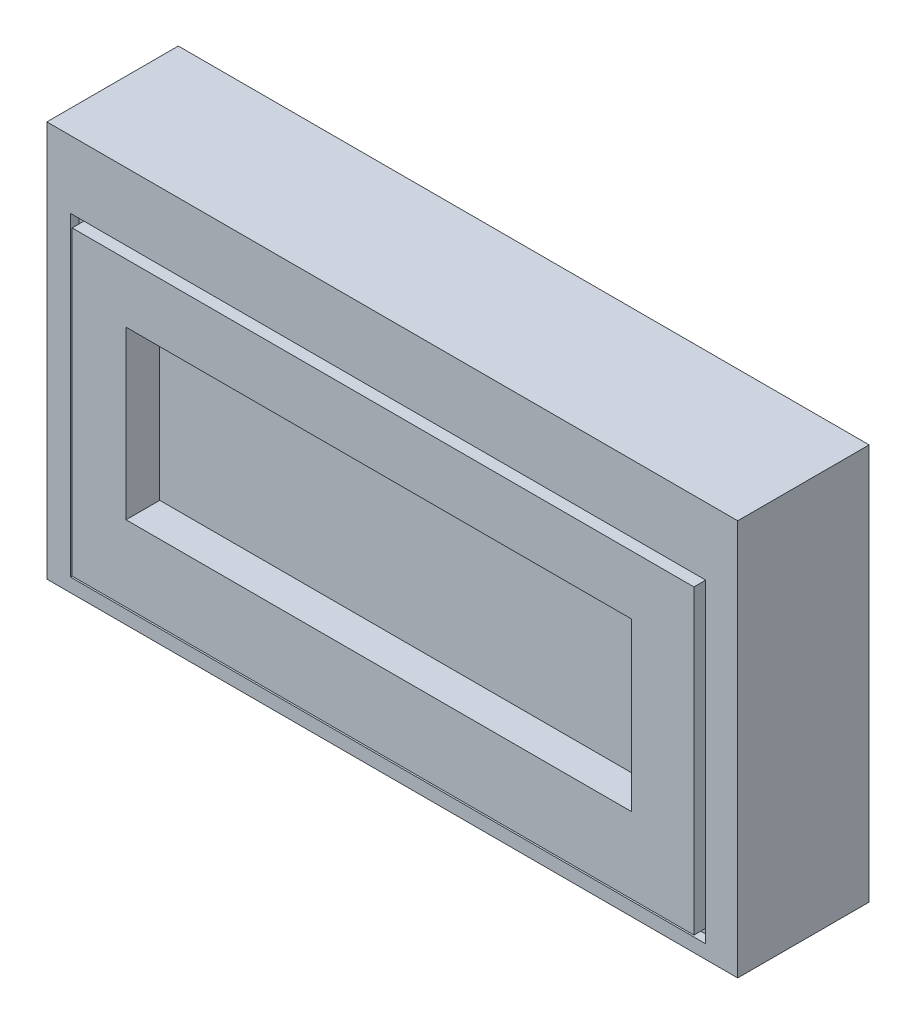
SolidWorks part; units mm, degrees
ref_plane "Alzado" through (0, 0, 0) normal (0, 0, 1) x (1, 0, 0)
ref_plane "Planta" through (0, 0, 0) normal (0, 1, 0) x (1, 0, 0)
ref_plane "Vista lateral" through (0, 0, 0) normal (1, 0, 0) x (0, 0, -1)
sketch "Croquis1" plane through (0, 0, 0) normal (0, 0, 1) x (1, 0, 0)
  line L1 (-43.4234, 226.9304) -> (366.5766, 226.9304)
  line L2 (-43.4234, 226.9304) -> (-43.4234, -8.0696)
  line L3 (-43.4234, -8.0696) -> (366.5766, -8.0696)
  line L4 (366.5766, 226.9304) -> (366.5766, -8.0696)
extrude "Saliente-Extruir1" add sketch "Croquis1" along normal blind 78
sketch "Croquis2" plane through (0, 0, 78) normal (0, 0, 1) x (1, 0, 0)
  line L0 (154.0772, 186.9304) -> (154.0772, 226.9304) construction
  line L1 (366.5766, 226.9304) -> (-43.4234, 226.9304) construction
  line L2 (366.5766, 109.4304) -> (347.5766, 109.4304) construction
  line L3 (366.5766, -8.0696) -> (366.5766, 226.9304) construction
  line L4 (161.5766, -8.0696) -> (161.5766, 0.9304) construction
  line L5 (-43.4234, -8.0696) -> (366.5766, -8.0696) construction
  line L6 (-43.4234, 109.4304) -> (-29.4234, 109.4304) construction
  line L7 (-43.4234, 226.9304) -> (-43.4234, -8.0696) construction
  line L8 (347.5766, 186.9304) -> (-29.4234, 186.9304)
  line L9 (-29.4234, 186.9304) -> (-29.4234, 0)
  line L10 (-29.4234, 0) -> (347.5766, 0)
  line L11 (347.5766, 0) -> (347.5766, 186.9304)
extrude "Cortar-Extruir1" cut sketch "Croquis2" against normal blind 5
sketch "Croquis3" plane through (0, 0, 73) normal (0, 0, 1) x (1, 0, 0)
  line L0 (343.5766, 182.9304) -> (-25.4234, 4) construction
  line L1 (-25.4234, 182.9304) -> (343.5766, 182.9304)
  line L2 (-25.4234, 182.9304) -> (-25.4234, 4)
  line L3 (-25.4234, 4) -> (343.5766, 4)
  line L4 (343.5766, 182.9304) -> (343.5766, 4)
  line L5 (347.5766, 186.9304) -> (-29.4234, 0) construction
  line L6 (159.0766, 93.4652) -> (179.0059, 93.4652) construction
  line L7 (179.0059, 93.4652) -> (139.6808, 93.4652) construction
  line L8 (347.5766, 0) -> (347.5766, 186.9304) construction
  line L9 (-29.4234, 0) -> (347.5766, 0) construction
  line L10 (347.5766, 186.9304) -> (-29.4234, 186.9304) construction
  line L11 (-29.4234, 186.9304) -> (-29.4234, 0) construction
  dimension "D1" = 4
  dimension "D2" = 4
  dimension "D3" = 4
  dimension "D4" = 4
extrude "Saliente-Extruir2" add sketch "Croquis3" along normal blind 8
sketch "Croquis4" plane through (0, 0, 78) normal (0, 0, 1) x (1, 0, 0)
  line L0 (-43.4234, -8.0696) -> (55.5766, -8.0696) construction
  line L1 (-43.4234, -8.0696) -> (366.5766, -8.0696) construction
  line L2 (55.5766, -8.0696) -> (55.5766, 92.9304) construction
  circle A0 centre (55.5766, 92.9304) radius 1
sketch "Croquis5" plane through (0, 0, 81) normal (0, 0, 1) x (1, 0, 0)
  line L0 (55.5766, 92.9304) -> (55.5766, 48.9304) construction
  line L1 (55.5766, -8.0696) -> (55.5766, 92.9304) construction
  line L2 (55.5766, 48.9304) -> (6.5766, 48.9304) construction
  line L4 (6.5766, 48.9304) -> (306.5766, 48.9304)
  line L5 (6.5766, 48.9304) -> (6.5766, 147.9304)
  line L6 (6.5766, 147.9304) -> (306.5766, 147.9304)
  line L7 (306.5766, 48.9304) -> (306.5766, 147.9304)
extrude "Cortar-Extruir2" cut sketch "Croquis5" against normal blind 20
